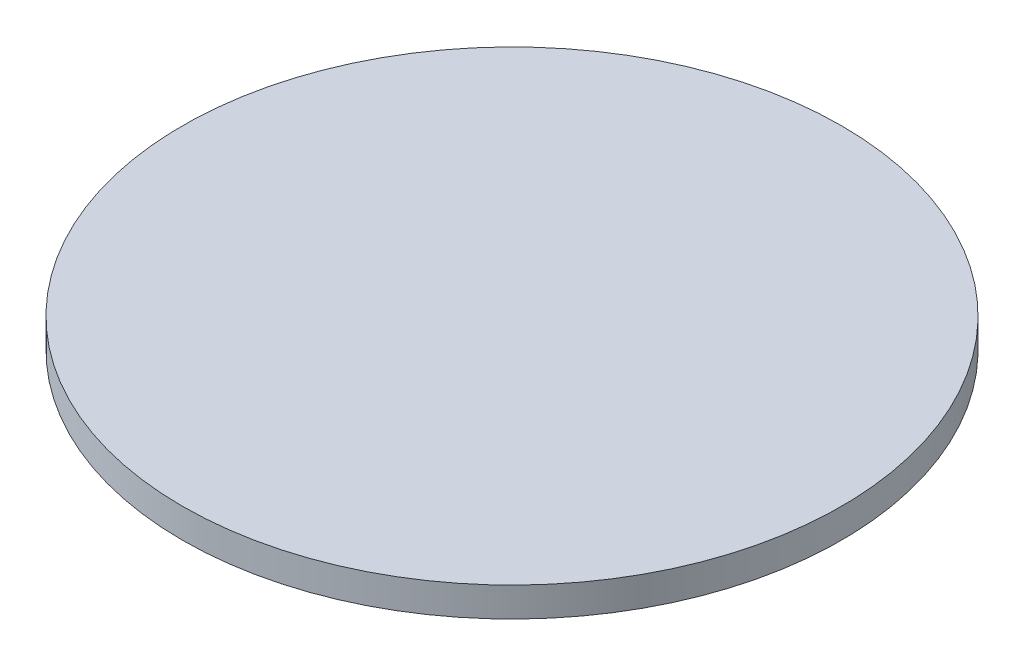
SolidWorks part; units mm, degrees
ref_plane "Front Plane" through (0, 0, 0) normal (0, 0, 1) x (1, 0, 0)
ref_plane "Top Plane" through (0, 0, 0) normal (0, 1, 0) x (1, 0, 0)
ref_plane "Right Plane" through (0, 0, 0) normal (1, 0, 0) x (0, 0, -1)
sketch "Sketch1" plane through (0, 0, 0) normal (0, 1, 0) x (1, 0, 0)
  circle A0 centre (0, 0) radius 1066.8
extrude "Boss-Extrude1" add sketch "Sketch1" along normal blind 95.25
sketch "Sketch2" plane through (0, 0, 0) normal (0, -1, 0) x (1, 0, 0)
  circle A0 centre (-180.975, -313.4579) radius 24.25
  circle A1 centre (-120.65, -313.4579) radius 24.25
  circle A2 centre (-60.325, -313.4579) radius 24.25
  circle A3 centre (0, -313.4579) radius 24.25
  circle A4 centre (60.325, -313.4579) radius 24.25
  circle A5 centre (120.65, -313.4579) radius 24.25
  circle A6 centre (180.975, -313.4579) radius 24.25
  circle A7 centre (-271.4625, -261.2149) radius 24.25
  circle A8 centre (-211.1375, -261.2149) radius 30.1625
  circle A9 centre (-150.8125, -261.2149) radius 30.1625
  circle A10 centre (-90.4875, -261.2149) radius 30.1625
  circle A11 centre (-30.1625, -261.2149) radius 30.1625
  circle A12 centre (30.1625, -261.2149) radius 30.1625
  circle A13 centre (90.4875, -261.2149) radius 30.1625
  circle A14 centre (150.8125, -261.2149) radius 30.1625
  circle A15 centre (211.1375, -261.2149) radius 24.25
  circle A16 centre (271.4625, -261.2149) radius 24.25
  circle A17 centre (-301.625, -208.9719) radius 30.1625
  circle A18 centre (-241.3, -208.9719) radius 30.1625
  circle A19 centre (-180.975, -208.9719) radius 30.1625
  circle A20 centre (-120.65, -208.9719) radius 30.1625
  circle A21 centre (-60.325, -208.9719) radius 30.1625
  circle A22 centre (0, -208.9719) radius 30.1625
  circle A23 centre (60.325, -208.9719) radius 30.1625
  circle A24 centre (120.65, -208.9719) radius 30.1625
  circle A25 centre (180.975, -208.9719) radius 30.1625
  circle A26 centre (241.3, -208.9719) radius 30.1625
  circle A27 centre (301.625, -208.9719) radius 24.25
  circle A28 centre (-331.7875, -156.7289) radius 30.1625
  circle A29 centre (-271.4625, -156.7289) radius 30.1625
  circle A30 centre (-211.1375, -156.7289) radius 30.1625
  circle A31 centre (-150.8125, -156.7289) radius 30.1625
  circle A32 centre (-90.4875, -156.7289) radius 30.1625
  circle A33 centre (-30.1625, -156.7289) radius 30.1625
  circle A34 centre (30.1625, -156.7289) radius 30.1625
  circle A35 centre (90.4875, -156.7289) radius 30.1625
  circle A36 centre (150.8125, -156.7289) radius 30.1625
  circle A37 centre (211.1375, -156.7289) radius 30.1625
  circle A38 centre (271.4625, -156.7289) radius 30.1625
  circle A39 centre (331.7875, -156.7289) radius 24.25
  circle A40 centre (-361.95, -104.486) radius 30.1625
  circle A41 centre (-301.625, -104.486) radius 30.1625
  circle A42 centre (-241.3, -104.486) radius 30.1625
  circle A43 centre (-180.975, -104.486) radius 30.1625
  circle A44 centre (-120.65, -104.486) radius 30.1625
  circle A45 centre (-60.325, -104.486) radius 30.1625
  circle A46 centre (0, -104.486) radius 30.1625
  circle A47 centre (60.325, -104.486) radius 30.1625
  circle A48 centre (120.65, -104.486) radius 30.1625
  circle A49 centre (180.975, -104.486) radius 30.1625
  circle A50 centre (241.3, -104.486) radius 30.1625
  circle A51 centre (301.625, -104.486) radius 30.1625
  circle A52 centre (361.95, -104.486) radius 24.25
  circle A53 centre (-331.7875, -52.243) radius 30.1625
  circle A54 centre (-271.4625, -52.243) radius 30.1625
  circle A55 centre (-211.1375, -52.243) radius 30.1625
  circle A56 centre (-150.8125, -52.243) radius 30.1625
  circle A57 centre (-90.4875, -52.243) radius 30.1625
  circle A58 centre (-30.1625, -52.243) radius 30.1625
  circle A59 centre (30.1625, -52.243) radius 30.1625
  circle A60 centre (90.4875, -52.243) radius 30.1625
  circle A61 centre (150.8125, -52.243) radius 30.1625
  circle A62 centre (211.1375, -52.243) radius 30.1625
  circle A63 centre (271.4625, -52.243) radius 30.1625
  circle A64 centre (331.7875, -52.243) radius 30.1625
  circle A65 centre (-361.95, 0) radius 30.1625
  circle A66 centre (-301.625, 0) radius 30.1625
  circle A67 centre (-241.3, 0) radius 30.1625
  circle A68 centre (-180.975, 0) radius 30.1625
  circle A69 centre (-120.65, 0) radius 30.1625
  circle A70 centre (-60.325, 0) radius 30.1625
  circle A71 centre (0, 0) radius 30.1625
  circle A72 centre (60.325, 0) radius 30.1625
  circle A73 centre (120.65, 0) radius 30.1625
  circle A74 centre (180.975, 0) radius 30.1625
  circle A75 centre (241.3, 0) radius 30.1625
  circle A76 centre (301.625, 0) radius 30.1625
  circle A77 centre (361.95, 0) radius 24.25
  circle A78 centre (-331.7875, 52.243) radius 30.1625
  circle A79 centre (-271.4625, 52.243) radius 30.1625
  circle A80 centre (-211.1375, 52.243) radius 30.1625
  circle A81 centre (-150.8125, 52.243) radius 30.1625
  circle A82 centre (-90.4875, 52.243) radius 30.1625
  circle A83 centre (-30.1625, 52.243) radius 30.1625
  circle A84 centre (30.1625, 52.243) radius 30.1625
  circle A85 centre (90.4875, 52.243) radius 30.1625
  circle A86 centre (150.8125, 52.243) radius 30.1625
  circle A87 centre (211.1375, 52.243) radius 30.1625
  circle A88 centre (271.4625, 52.243) radius 30.1625
  circle A89 centre (331.7875, 52.243) radius 30.1625
  circle A90 centre (-361.95, 104.486) radius 30.1625
  circle A91 centre (-301.625, 104.486) radius 30.1625
  circle A92 centre (-241.3, 104.486) radius 30.1625
  circle A93 centre (-180.975, 104.486) radius 30.1625
  circle A94 centre (-120.65, 104.486) radius 30.1625
  circle A95 centre (-60.325, 104.486) radius 30.1625
  circle A96 centre (0, 104.486) radius 30.1625
  circle A97 centre (60.325, 104.486) radius 30.1625
  circle A98 centre (120.65, 104.486) radius 30.1625
  circle A99 centre (180.975, 104.486) radius 30.1625
  circle A100 centre (241.3, 104.486) radius 30.1625
  circle A101 centre (301.625, 104.486) radius 30.1625
  circle A102 centre (361.95, 104.486) radius 24.25
  circle A103 centre (-331.7875, 156.7289) radius 30.1625
  circle A104 centre (-271.4625, 156.7289) radius 30.1625
  circle A105 centre (-211.1375, 156.7289) radius 30.1625
  circle A106 centre (-150.8125, 156.7289) radius 30.1625
  circle A107 centre (-90.4875, 156.7289) radius 30.1625
  circle A108 centre (-30.1625, 156.7289) radius 30.1625
  circle A109 centre (30.1625, 156.7289) radius 30.1625
  circle A110 centre (90.4875, 156.7289) radius 30.1625
  circle A111 centre (150.8125, 156.7289) radius 30.1625
  circle A112 centre (211.1375, 156.7289) radius 30.1625
  circle A113 centre (271.4625, 156.7289) radius 30.1625
  circle A114 centre (331.7875, 156.7289) radius 30.1625
  circle A115 centre (-301.625, 208.9719) radius 30.1625
  circle A116 centre (-241.3, 208.9719) radius 30.1625
  circle A117 centre (-180.975, 208.9719) radius 30.1625
  circle A118 centre (-120.65, 208.9719) radius 30.1625
  circle A119 centre (-60.325, 208.9719) radius 30.1625
  circle A120 centre (0, 208.9719) radius 30.1625
  circle A121 centre (60.325, 208.9719) radius 30.1625
  circle A122 centre (120.65, 208.9719) radius 30.1625
  circle A123 centre (180.975, 208.9719) radius 30.1625
  circle A124 centre (241.3, 208.9719) radius 30.1625
  circle A125 centre (301.625, 208.9719) radius 30.1625
  circle A126 centre (-271.4625, 261.2149) radius 30.1625
  circle A127 centre (-211.1375, 261.2149) radius 30.1625
  circle A128 centre (-150.8125, 261.2149) radius 30.1625
  circle A129 centre (-90.4875, 261.2149) radius 30.1625
  circle A130 centre (-30.1625, 261.2149) radius 30.1625
  circle A131 centre (30.1625, 261.2149) radius 30.1625
  circle A132 centre (90.4875, 261.2149) radius 30.1625
  circle A133 centre (150.8125, 261.2149) radius 30.1625
  circle A134 centre (211.1375, 261.2149) radius 30.1625
  circle A135 centre (271.4625, 261.2149) radius 30.1625
  circle A136 centre (-180.975, 313.4579) radius 30.1625
  circle A137 centre (-120.65, 313.4579) radius 30.1625
  circle A138 centre (-60.325, 313.4579) radius 30.1625
  circle A139 centre (0, 313.4579) radius 30.1625
  circle A140 centre (60.325, 313.4579) radius 30.1625
  circle A141 centre (120.65, 313.4579) radius 30.1625
  circle A142 centre (180.975, 313.4579) radius 30.1625
